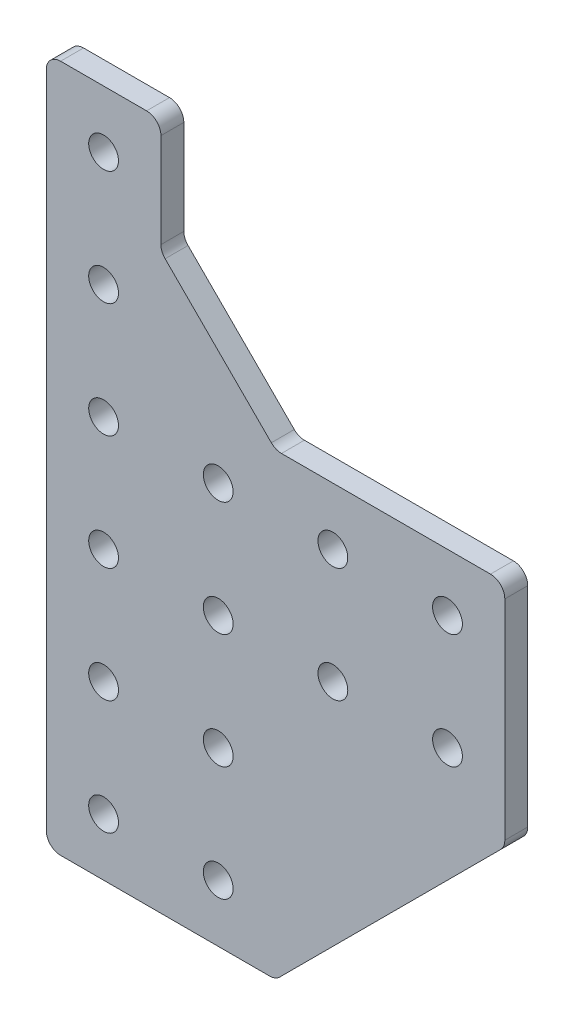
SolidWorks part; units mm, degrees
ref_plane "Спереди" through (0, 0, 0) normal (0, 0, 1) x (1, 0, 0)
ref_plane "Сверху" through (0, 0, 0) normal (0, 1, 0) x (1, 0, 0)
ref_plane "Справа" through (0, 0, 0) normal (1, 0, 0) x (0, 0, -1)
sketch "Эскиз1" plane through (0, 0, 0) normal (0, 0, 1) x (1, 0, 0)
  line L0 (40.7322, -79.2678) -> (79.2678, -40.7322)
  line L1 (41.0355, 0) -> (77.5, 0)
  line L2 (0, 0) -> (0, -77.5)
  line L3 (2.5, -80) -> (38.9645, -80)
  line L4 (80, -2.5) -> (80, -38.9645)
  line L5 (0, 0) -> (0, 37.5)
  line L6 (2.5, 40) -> (17.5, 40)
  line L7 (20, 37.5) -> (20, 21.0355)
  line L9 (20.7322, 19.2678) -> (39.2678, 0.7322)
  arc A1 (0, -77.5) -> (2.5, -80) centre (2.5, -77.5) ccw
  arc A2 (40.7322, -79.2678) -> (38.9645, -80) centre (38.9645, -77.5) cw
  arc A3 (80, -38.9645) -> (79.2678, -40.7322) centre (77.5, -38.9645) cw
  arc A4 (77.5, 0) -> (80, -2.5) centre (77.5, -2.5) cw
  circle A5 centre (10, -10) radius 2.6
  circle A6 centre (30, -10) radius 2.6
  circle A7 centre (30, -30) radius 2.6
  circle A8 centre (30, -50) radius 2.6
  circle A9 centre (30, -70) radius 2.6
  circle A10 centre (10, -30) radius 2.6
  circle A11 centre (10, -50) radius 2.6
  circle A12 centre (10, -70) radius 2.6
  circle A13 centre (50, -10) radius 2.6
  circle A14 centre (50, -30) radius 2.6
  circle A15 centre (70, -10) radius 2.6
  circle A16 centre (70, -30) radius 2.6
  circle A17 centre (10, 10) radius 2.6
  circle A18 centre (10, 30) radius 2.6
  arc A19 (20, 21.0355) -> (20.7322, 19.2678) centre (22.5, 21.0355) ccw
  arc A20 (39.2678, 0.7322) -> (41.0355, 0) centre (41.0355, 2.5) ccw
  arc A21 (17.5, 40) -> (20, 37.5) centre (17.5, 37.5) cw
  arc A22 (0, 37.5) -> (2.5, 40) centre (2.5, 37.5) cw
  point P8 (0, 0)
  point P11 (0, -80)
  point P14 (40, -80)
  point P52 (20, 20)
  point P57 (20, 40)
  point P60 (0, 40)
  dimension "D3" = 20
  dimension "D4" = 2.5
  dimension "D5" = 2.5
  dimension "D6" = 2.5
  dimension "D7" = 2.5
  dimension "D8" = 5.2
  dimension "D10" = 10
  dimension "D18" = 2.5
  dimension "D1" = 80
  dimension "D2" = 40
  dimension "D9" = 10
  dimension "D14" = 80
  dimension "D15" = 20
  dimension "D17" = 45
  dimension "D11" = 2
  dimension "D12" = 4
  dimension "D13" = 3
  dimension "D16" = 3
extrude "Бобышка-Вытянуть1" add sketch "Эскиз1" along normal blind 4
